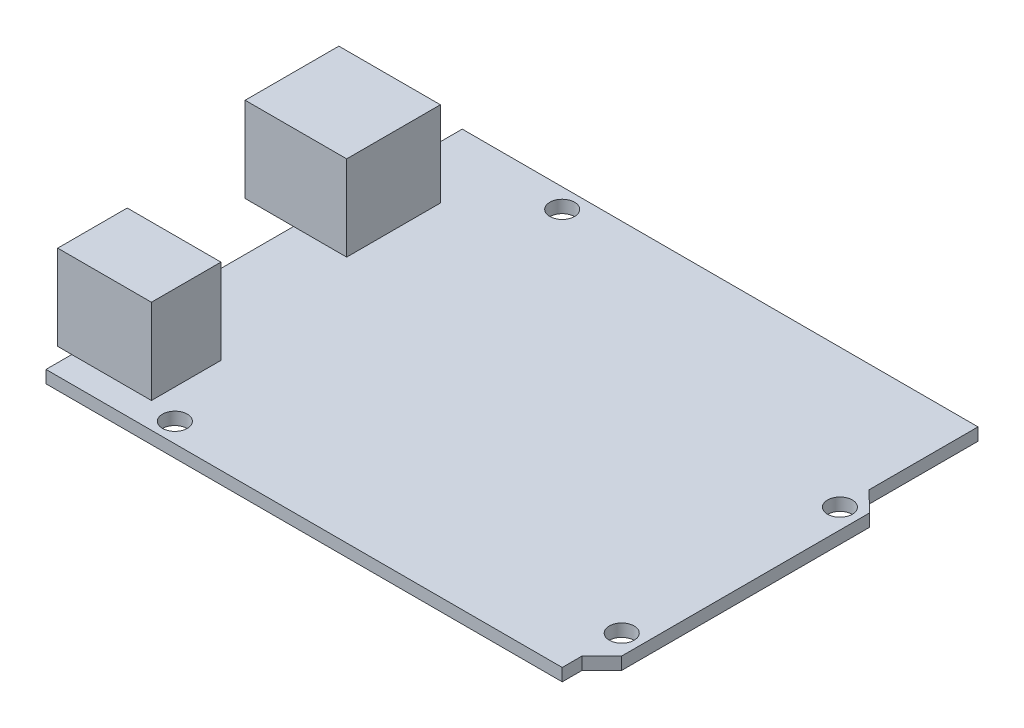
SolidWorks part; units mm, degrees
ref_plane "Front Plane" through (0, 0, 0) normal (0, 0, 1) x (1, 0, 0)
ref_plane "Top Plane" through (0, 0, 0) normal (0, 1, 0) x (1, 0, 0)
ref_plane "Right Plane" through (0, 0, 0) normal (1, 0, 0) x (0, 0, -1)
sketch "Sketch1" plane through (0, 0, 0) normal (0, 1, 0) x (1, 0, 0)
  line L0 (-34.3, -26.65) -> (-34.3, 26.65)
  line L1 (-34.3, -26.65) -> (31.8, -26.65)
  line L2 (31.8, -26.65) -> (31.8, -24.11)
  line L3 (34.34, -21.57) -> (34.34, 10.18)
  line L4 (31.8, -24.11) -> (34.34, -21.57)
  line L5 (-34.3, 26.65) -> (31.74, 26.65)
  line L6 (31.74, 26.65) -> (31.74, 12.68)
  line L7 (31.74, 12.68) -> (34.34, 10.18)
  circle A0 centre (-19, 24.15) radius 1.5875
  circle A1 centre (-20.3, -24.15) radius 1.5875
  circle A2 centre (31.8, 8.91) radius 1.5875
  circle A3 centre (31.8, -19.03) radius 1.5875
  point P2 (-34.3, 0)
  dimension "D11" = 3.175
  dimension "D12" = 15.3
  dimension "D13" = 50.8
  dimension "D14" = 3.175
  dimension "D15" = 2.5
  dimension "D16" = 1.3
  dimension "D18" = 3.175
  dimension "D19" = 35.56
  dimension "D20" = 2.54
  dimension "D21" = 3.175
  dimension "D23" = 7.62
  dimension "D24" = 27.94
  dimension "D1" = 34.3
  dimension "D2" = 53.3
  dimension "D3" = 0
  dimension "D4" = 66.1
  dimension "D5" = 2.54
  dimension "D6" = 31.75
  dimension "D7" = 2.54
  dimension "D8" = 2.54
  dimension "D9" = 66.04
  dimension "D10" = 13.97
extrude "Boss-Extrude1" add sketch "Sketch1" along normal blind 1.6
sketch "Sketch2" plane through (0, 1.6, 0) normal (0, 1, 0) x (1, 0, 0)
  line L0 (-34.3, -26.65) -> (31.8, -26.65) construction
  line L1 (-36.1, -23.35) -> (-24.1, -23.35)
  line L2 (-36.1, -23.35) -> (-36.1, -14.45)
  line L3 (-36.1, -14.45) -> (-24.1, -14.45)
  line L4 (-24.1, -23.35) -> (-24.1, -14.45)
  line L5 (-34.3, 26.65) -> (-34.3, -26.65) construction
  line L6 (31.74, 26.65) -> (-34.3, 26.65) construction
  line L7 (-40.5, 17.05) -> (-27.5, 17.05)
  line L8 (-40.5, 17.05) -> (-40.5, 5.05)
  line L9 (-40.5, 5.05) -> (-27.5, 5.05)
  line L10 (-27.5, 17.05) -> (-27.5, 5.05)
  dimension "D1" = 8.9
  dimension "D2" = 3.3
  dimension "D3" = 1.8
  dimension "D4" = 12
  dimension "D5" = 9.6
  dimension "D6" = 12
  dimension "D7" = 6.2
  dimension "D8" = 13
extrude "Boss-Extrude2" add sketch "Sketch2" along normal blind 10.9
